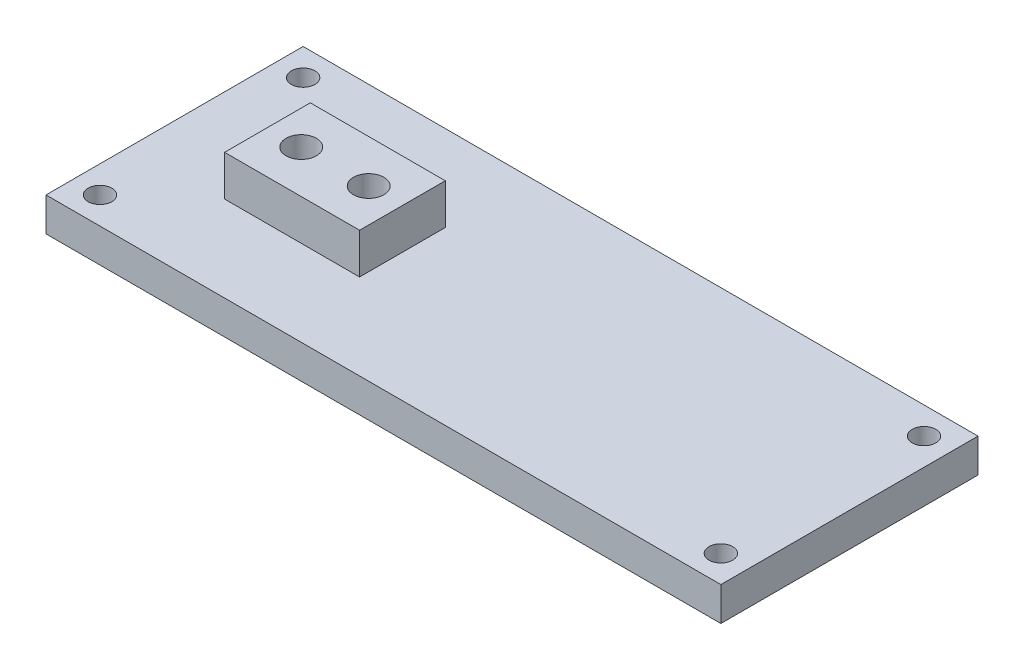
SolidWorks part; units mm, degrees
ref_plane "Front Plane" through (0, 0, 0) normal (0, 0, 1) x (1, 0, 0)
ref_plane "Top Plane" through (0, 0, 0) normal (0, 1, 0) x (1, 0, 0)
ref_plane "Right Plane" through (0, 0, 0) normal (1, 0, 0) x (0, 0, -1)
sketch "Sketch1" plane through (0, 0, 0) normal (0, 1, 0) x (1, 0, 0)
  line L1 (-50, 19.05) -> (50, 19.05)
  line L2 (-50, 19.05) -> (-50, -19.05)
  line L3 (-50, -19.05) -> (50, -19.05)
  line L4 (50, 19.05) -> (50, -19.05)
  line L5 (-50, 19.05) -> (50, -19.05) construction
  line L6 (-50, -19.05) -> (50, 19.05) construction
  point P0 (0, 0)
  dimension "D1" = 100
  dimension "D2" = 38.1
extrude "Boss-Extrude1" add sketch "Sketch1" along normal blind 5
sketch "Sketch2" plane through (0, 5, 0) normal (0, 1, 0) x (1, 0, 0)
  line L1 (-36.2366, 6.35) -> (-16.2366, 6.35)
  line L2 (-36.2366, 6.35) -> (-36.2366, -6.35)
  line L3 (-36.2366, -6.35) -> (-16.2366, -6.35)
  line L4 (-16.2366, 6.35) -> (-16.2366, -6.35)
  line L5 (-36.2366, 6.35) -> (-16.2366, -6.35) construction
  line L6 (-36.2366, -6.35) -> (-16.2366, 6.35) construction
  point P0 (-26.2366, 0)
  dimension "D1" = 12.7
  dimension "D2" = 20
extrude "Boss-Extrude2" add sketch "Sketch2" along normal blind 6
sketch "Sketch3" plane through (0, 11, 0) normal (0, 1, 0) x (1, 0, 0)
  line L0 (-36.2366, 6.35) -> (-36.2366, -6.35) construction
  circle A0 centre (-21.2366, 0) radius 2.25
  circle A1 centre (-31.2366, 0) radius 2.25
  point P4 (0, 0)
  dimension "D1" = 4.5
  dimension "D2" = 4.5
  dimension "D3" = 10
  dimension "D4" = 5
sketch "Sketch11" plane through (0, 11, 0) normal (0, 1, 0) x (1, 0, 0)
  point P0 (-31.2366, 0)
  point P3 (-21.2366, 0)
hole_wizard "Tap Drill for M4x0.7 Tap1" positions "Sketch11" profile "Sketch10" hole size "M4x0.7" standard "ANSI Metric" end condition through all
sketch "Sketch10" plane through (-31.2366, 11, 0) normal (1, 0, 0) x (0, 0, 1)
  line L0 (0, 0) -> (0, 11)
  line L1 (0, 11) -> (1.65, 11)
  line L2 (1.65, 11) -> (1.65, 0)
  line L5 (1.65, 0) -> (0, 0)
  line L11 (0, -6.35) -> (0, 107.95) construction
  dimension "Thru Hole Dia." = 3.3
  dimension "Thru Hole Depth" = 11
extrude "Cut-Extrude1" cut sketch "Sketch3" against normal through all
sketch "Sketch12" plane through (0, 0, 0) normal (0, -1, 0) x (1, 0, 0)
  circle A0 centre (-31.2366, 0) radius 4.5
  circle A1 centre (-21.2366, 0) radius 4.5
  dimension "D1" = 9
  dimension "D2" = 9
extrude "Cut-Extrude2" cut sketch "Sketch12" against normal blind 3
sketch "Sketch13" plane through (0, 5, 0) normal (0, 1, 0) x (1, 0, 0)
  line L0 (50, 19.05) -> (-50, 19.05) construction
  line L1 (-50, -19.05) -> (50, -19.05) construction
  line L2 (-50, 19.05) -> (-50, -19.05) construction
  line L3 (0, -19.05) -> (0, 19.05) construction
  circle A0 centre (-46, 15.05) radius 1.75
  circle A1 centre (-46, -15.05) radius 1.75
  circle A2 centre (46, -15.05) radius 1.75
  circle A3 centre (46, 15.05) radius 1.75
  dimension "D5" = 3.5
  dimension "D6" = 3.5
  dimension "D1" = 4
  dimension "D2" = 4
  dimension "D3" = 4
  dimension "D4" = 4
extrude "Cut-Extrude3" cut sketch "Sketch13" against normal blind 10
